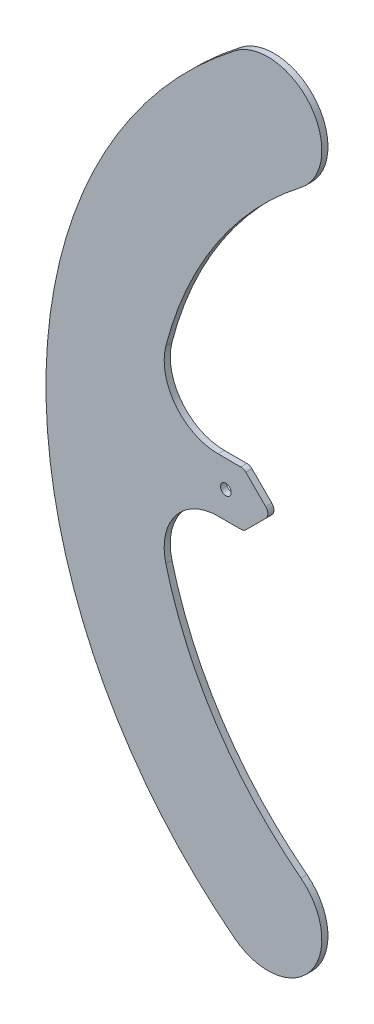
SolidWorks part; units mm, degrees
ref_plane "Front Plane" through (0, 0, 0) normal (0, 0, 1) x (1, 0, 0)
ref_plane "Top Plane" through (0, 0, 0) normal (0, 1, 0) x (1, 0, 0)
ref_plane "Right Plane" through (0, 0, 0) normal (1, 0, 0) x (0, 0, -1)
sketch "Sketch1" plane through (0, 0, 0) normal (0, 0, 1) x (1, 0, 0)
  line L0 (-32.8019, 0) -> (18.2589, 0) construction
  line L1 (70.5, 105) -> (70.5, 135) construction
  line L2 (205.5, -110) -> (-64.5, -110)
  line L3 (205.5, -110) -> (205.5, 110)
  line L4 (205.5, 110) -> (-64.5, 110)
  line L5 (-19.5, 6) -> (-19.5, -6)
  line L6 (-18, -7.5) -> (-9.5, -7.5)
  line L7 (-9.5, -7.5) -> (-2, 0)
  line L8 (-2, 0) -> (-9.5, 7.5)
  line L9 (-9.5, 7.5) -> (-18, 7.5)
  line L10 (-19.5, 6) -> (-19.5, -6)
  line L11 (-18, -7.5) -> (-9.5, -7.5)
  line L12 (-9.5, -7.5) -> (-2, 0)
  line L13 (-2, 0) -> (-9.5, 7.5)
  line L14 (-9.5, 7.5) -> (-18, 7.5)
  line L15 (-64.5, -110) -> (-64.5, 110)
  line L16 (205.5, -110) -> (-64.5, 110) construction
  line L17 (205.5, 110) -> (-64.5, -110) construction
  line L18 (-18, 7.5) -> (-34.2318, 7.5)
  line L19 (-18, -7.5) -> (-34.2318, -7.5)
  circle A0 centre (-14.5, 0) radius 1.5 construction
  arc A2 (-19.5, -6) -> (-18, -7.5) centre (-18, -6) ccw
  arc A3 (-18, 7.5) -> (-19.5, 6) centre (-18, 6) ccw
  arc A4 (-19.5, -6) -> (-18, -7.5) centre (-18, -6) ccw
  arc A5 (-18, 7.5) -> (-19.5, 6) centre (-18, 6) ccw
  circle A6 centre (-14.5, 0) radius 1.5
  circle A7 centre (-14.5, 0) radius 1.5
  circle A8 centre (70.5, 0) radius 135
  circle A9 centre (70.5, 0) radius 105
  circle A11 centre (-2.8144, 95) radius 15
  circle A12 centre (-2.8144, -95) radius 15
  point P19 (-64.5, 0)
  point P27 (70.5, 110)
  dimension "D3" = 270
  dimension "D5" = 30
  dimension "D2" = 55
  dimension "D4" = 220
  dimension "D1" = 0
extrude "Boss-Extrude1" add sketch "Sketch1" along normal blind 1.7 contours A11 | A8 A12 A9 A11 | A12 | L18 A9 L19 A4 L10 A5 | L14 A5 L10 A4 L11 L12 L13 A6
fillet "Fillet1" radius 15 2 edges at (-34.2318, -7.5, 0.85) (-34.2318, 7.5, 0.85)
fillet "Fillet2" radius 2 3 edges at (-9.5, -7.5, 0.85) (-9.5, 7.5, 0.85) (-2, 0, 0.85)
